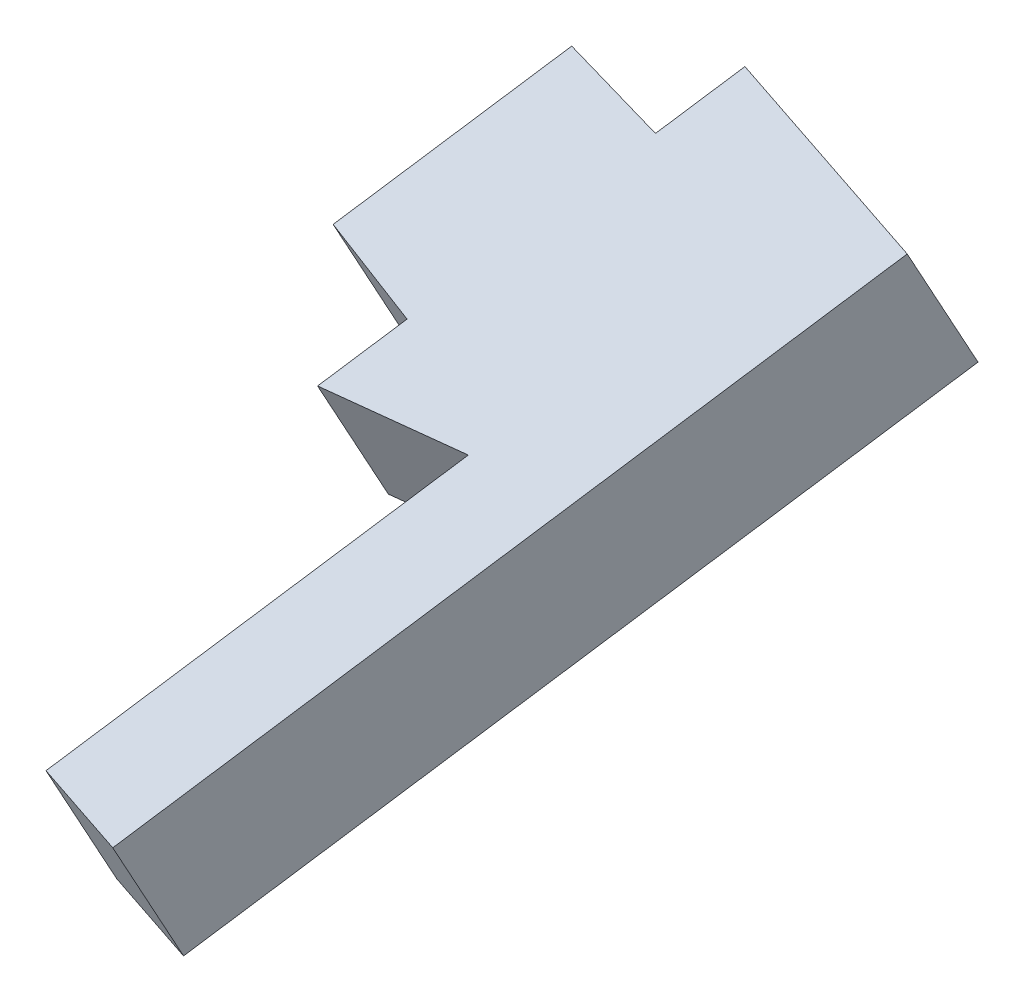
SolidWorks part; units mm, degrees
ref_plane "Front Plane" through (0, 0, 0) normal (0, 0, 1) x (1, 0, 0)
ref_plane "Top Plane" through (0, 0, 0) normal (0, 1, 0) x (1, 0, 0)
ref_plane "Right Plane" through (0, 0, 0) normal (1, 0, 0) x (0, 0, -1)
ref_plane "Plane1" through (-30.2839, 190.5651, 90.8517) normal (-0.142, 0.8935, 0.426) x (0.9896, 0.1388, 0.0388)
sketch "Sketch1" plane through (-30.2839, 190.5651, 90.8517) normal (-0.142, 0.8935, 0.426) x (0.9896, 0.1388, 0.0388)
  line L0 (3.0479, 175.2002) -> (-23.3429, 93.9782) construction
  line L1 (3.0479, 175.2002) -> (-23.3429, 93.9782) construction
  line L2 (-2.6585, 177.0543) -> (-29.0492, 95.8323) construction
  line L3 (-2.6585, 177.0543) -> (-29.0492, 95.8323) construction
  line L4 (-20.6446, 121.699) -> (-17.505, 131.3617)
  line L5 (-17.505, 131.3617) -> (-11.7339, 129.7069)
  line L6 (-20.6446, 121.699) -> (-15.003, 119.6456)
  line L7 (-15.003, 119.6456) -> (-16.1804, 116.0221)
  line L8 (-16.1804, 116.0221) -> (-8.5403, 116.0097)
  line L9 (-17.995, 91.0209) -> (-11.7678, 110.1862) construction
  line L10 (-17.995, 91.0209) -> (-11.2016, 111.9288) construction
  line L11 (-8.5403, 116.0097) -> (-14.0975, 98.9062)
  line L12 (-17.4168, 92.8005) -> (-16.2865, 96.2791) construction
  line L13 (-17.4168, 92.8005) -> (-16.2865, 96.2791) construction
  line L15 (-22.2302, 136.2354) -> (-16.5238, 134.3813) construction
  line L16 (-11.7339, 129.7069) -> (-10.5565, 133.3304)
  line L17 (-10.5565, 133.3304) -> (1.189, 129.514)
  line L18 (1.189, 129.514) -> (-9.2662, 97.3364)
  line L19 (-9.2662, 97.3364) -> (-14.0975, 98.9062)
  dimension "D1" = 3.175
  dimension "D2" = 10.16
  dimension "D3" = 92
  dimension "D4" = 3.81
  dimension "D5" = 5.08
  dimension "D6" = 3.175
  dimension "D7" = 72.093
  dimension "D8" = 1.27
extrude "Boss-Extrude1" add sketch "Sketch1" along normal mid plane 6
